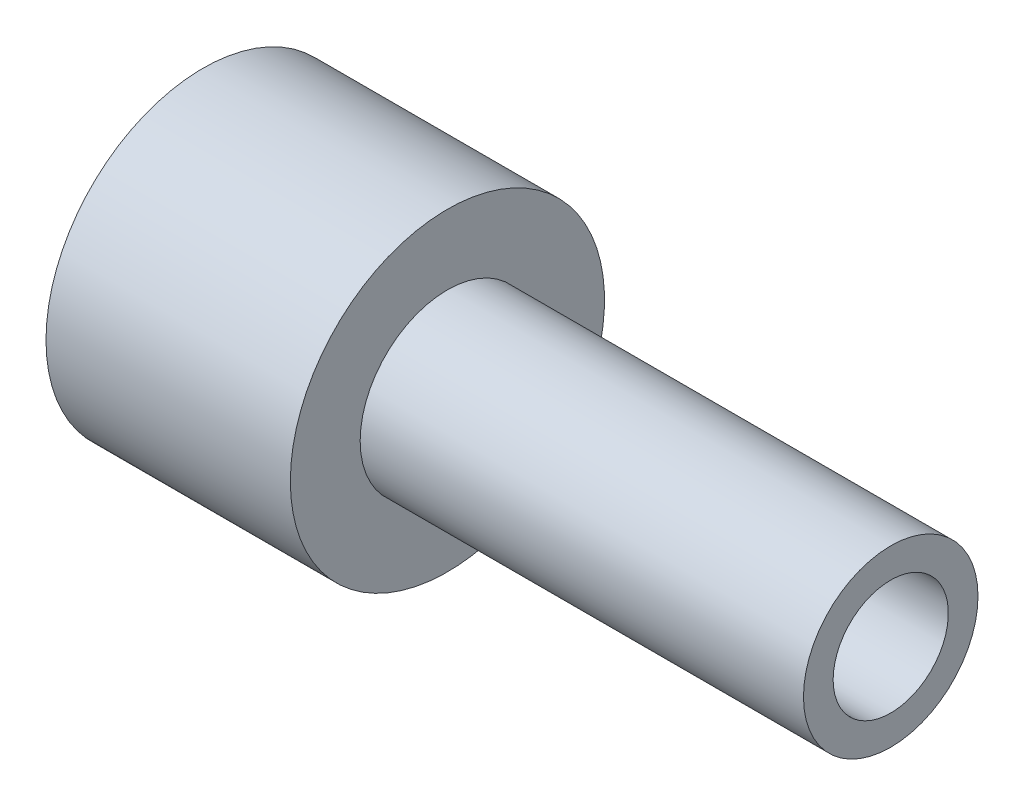
SolidWorks part; units mm, degrees
ref_plane "Front Plane" through (0, 0, 0) normal (0, 0, 1) x (1, 0, 0)
ref_plane "Top Plane" through (0, 0, 0) normal (0, 1, 0) x (1, 0, 0)
ref_plane "Right Plane" through (0, 0, 0) normal (1, 0, 0) x (0, 0, -1)
sketch "Axial profile (mm)" plane through (0, 0, 0) normal (0, 0, 1) x (1, 0, 0)
  line L0 (-110, 0) -> (75, 0) construction
  line L1 (-6, 1.65) -> (13.7, 1.65)
  line L2 (13.7, 1.65) -> (13.7, 2.5)
  line L3 (13.7, 2.5) -> (1, 2.5)
  line L4 (1, 2.5) -> (1, 4.5)
  line L5 (1, 4.5) -> (-6, 4.5)
  line L6 (-6, 4.5) -> (-6, 1.65)
revolve "Full revolution" add sketch "Axial profile (mm)" angle 360 about L0
